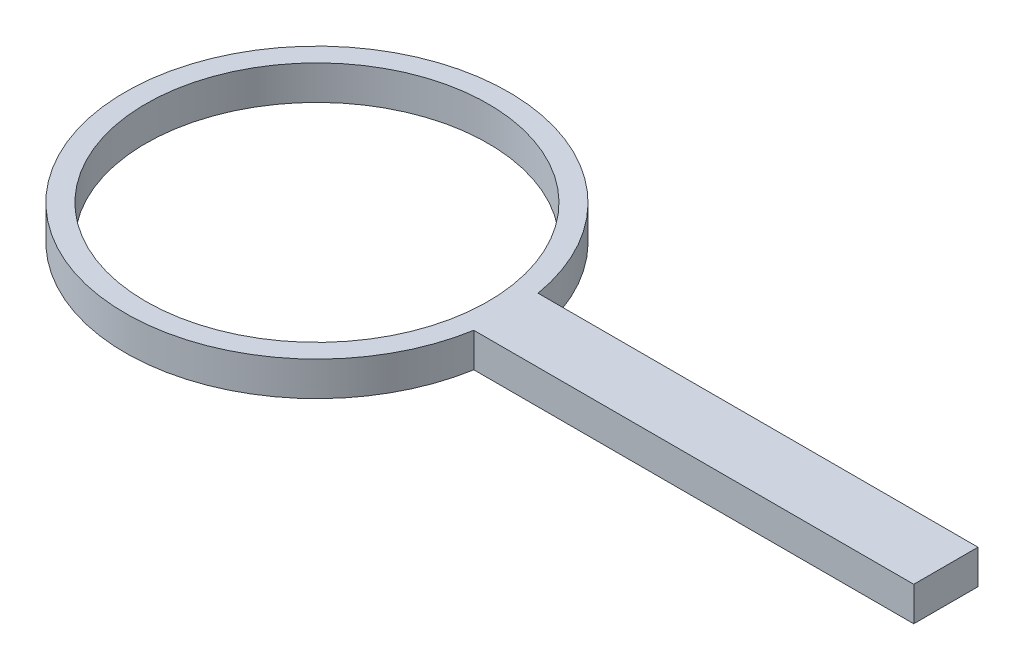
SolidWorks part; units mm, degrees
ref_plane "Plan de face" through (0, 0, 0) normal (0, 0, 1) x (1, 0, 0)
ref_plane "Plan de dessus" through (0, 0, 0) normal (0, 1, 0) x (1, 0, 0)
ref_plane "Plan de droite" through (0, 0, 0) normal (1, 0, 0) x (0, 0, -1)
sketch "Esquisse5" plane through (0, 5, 0) normal (0, 1, 0) x (1, 0, 0)
  circle A0 centre (-36.6073, 0) radius 28
extrude "Boss.-Extru.5" add sketch "Esquisse5" against normal blind 5 contours A0
sketch "Esquisse6" plane through (0, 5, 0) normal (0, 1, 0) x (1, 0, 0)
  circle A0 centre (-36.6073, 0) radius 25
extrude "Enlèv. mat.-Extru.1" cut sketch "Esquisse6" against normal blind 10
sketch "Esquisse7" plane through (0, 5, 0) normal (0, 1, 0) x (1, 0, 0)
  line L0 (55.2548, 4.6913) -> (-9.7452, 4.6913)
  line L1 (55.2548, 4.6913) -> (55.2548, -4.6913)
  line L2 (-9.7452, 4.6913) -> (-9.7452, -4.6913)
  line L3 (55.2548, -4.6913) -> (-9.7452, -4.6913)
  line L4 (55.2548, 4.6913) -> (-9.7452, -4.6913) construction
  line L5 (-9.7452, 4.6913) -> (55.2548, -4.6913) construction
  point P1 (22.7548, 0)
extrude "Boss.-Extru.6" add sketch "Esquisse7" against normal blind 5
